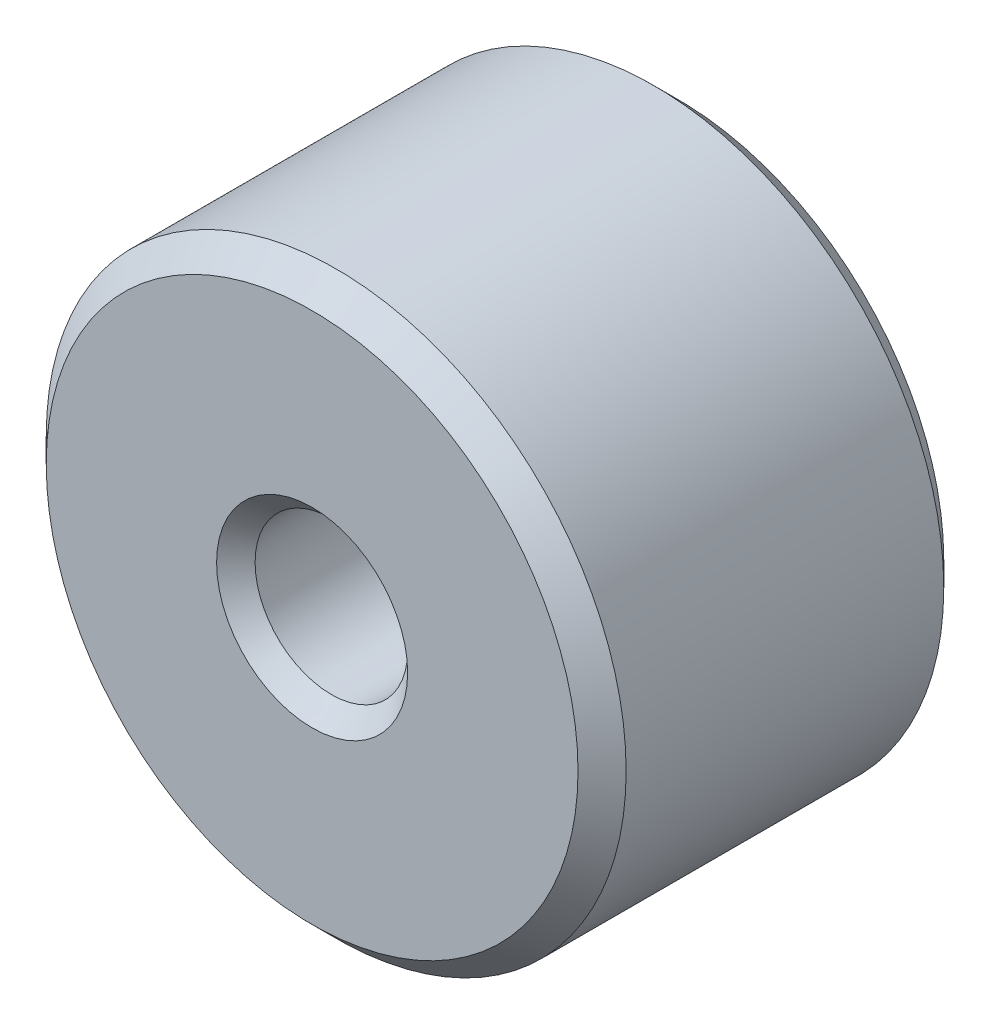
SolidWorks part; units mm, degrees
ref_plane "Front Plane" through (0, 0, 0) normal (0, 0, 1) x (1, 0, 0)
ref_plane "Top Plane" through (0, 0, 0) normal (0, 1, 0) x (1, 0, 0)
ref_plane "Right Plane" through (0, 0, 0) normal (1, 0, 0) x (0, 0, -1)
sketch "Sketch1" plane through (0, 0, 0) normal (0, 0, 1) x (1, 0, 0)
  circle A0 centre (0, 0) radius 6.025
  circle A1 centre (0, 0) radius 1.585
  dimension "D1" = 3.17
  dimension "D2" = 12.05
extrude "Boss-Extrude1" add sketch "Sketch1" along normal blind 7.6
chamfer "Chamfer1" distance 0.5 angle 45 2 edges at (6.025, 0, 7.6) (6.025, 0, 0)
chamfer "Chaflán1" distance 0.4 angle 45 1 edges at (1.585, 0, 7.6)
chamfer "Chaflán2" distance 1 angle 45 1 edges at (1.585, 0, 0)
